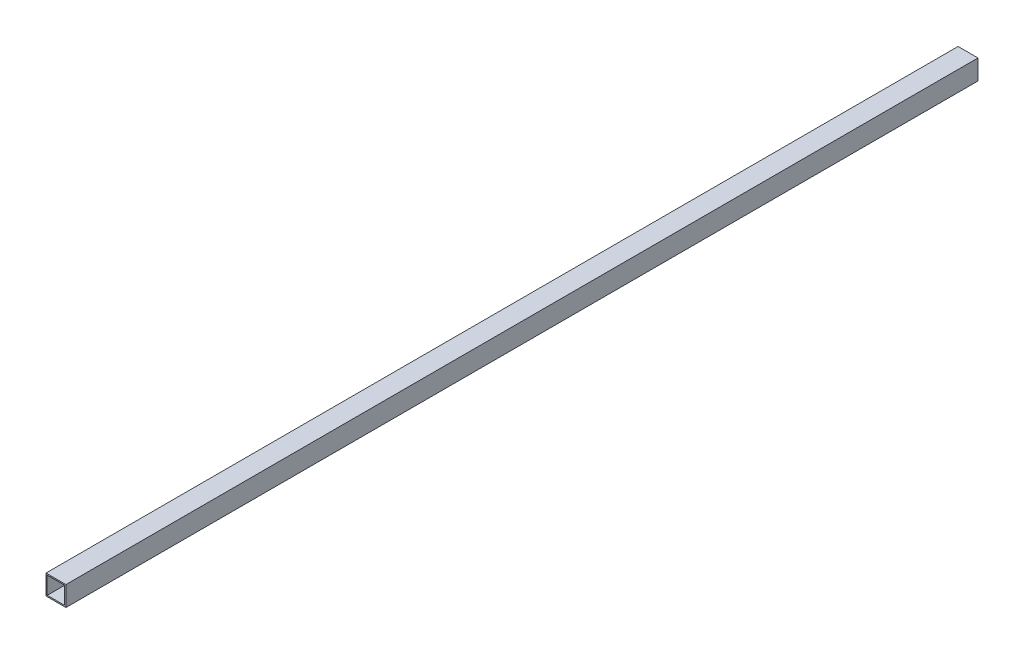
SolidWorks part; units mm, degrees
ref_plane "Front Plane" through (0, 0, 0) normal (0, 0, 1) x (1, 0, 0)
ref_plane "Top Plane" through (0, 0, 0) normal (0, 1, 0) x (1, 0, 0)
ref_plane "Right Plane" through (0, 0, 0) normal (1, 0, 0) x (0, 0, -1)
sketch "Sketch1" plane through (0, 0, 0) normal (0, 0, 1) x (1, 0, 0)
  line L1 (-25.4, 25.4) -> (25.4, 25.4)
  line L2 (-25.4, 25.4) -> (-25.4, -25.4)
  line L3 (-25.4, -25.4) -> (25.4, -25.4)
  line L4 (25.4, 25.4) -> (25.4, -25.4)
  line L5 (-25.4, 25.4) -> (25.4, -25.4) construction
  line L6 (-25.4, -25.4) -> (25.4, 25.4) construction
  line L7 (-22.225, 22.225) -> (22.225, 22.225)
  line L8 (-22.225, 22.225) -> (-22.225, -22.225)
  line L9 (-22.225, -22.225) -> (22.225, -22.225)
  line L10 (22.225, 22.225) -> (22.225, -22.225)
  line L11 (-22.225, 22.225) -> (22.225, -22.225) construction
  line L12 (-22.225, -22.225) -> (22.225, 22.225) construction
  point P0 (0, 0)
  point P6 (0, 0)
  dimension "D1" = 50.8
  dimension "D2" = 50.8
  dimension "D3" = 3.175
extrude "Boss-Extrude1" add sketch "Sketch1" against normal blind 2324.1
